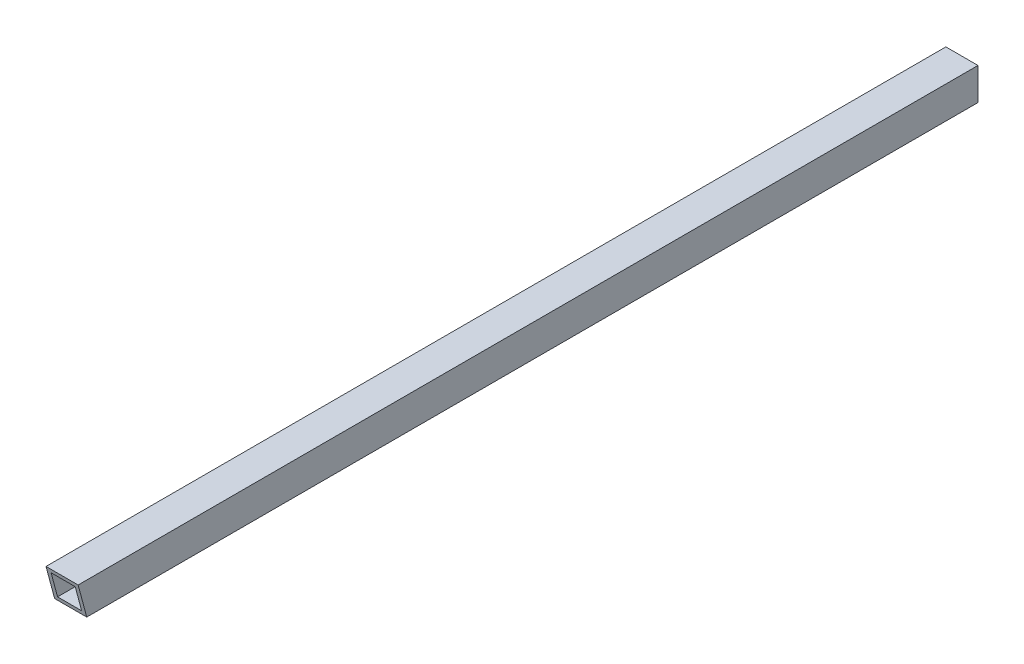
SolidWorks part; units mm, degrees
ref_plane "Front Plane" through (0, 0, 0) normal (0, 0, 1) x (1, 0, 0)
ref_plane "Top Plane" through (0, 0, 0) normal (0, 1, 0) x (1, 0, 0)
ref_plane "Right Plane" through (0, 0, 0) normal (1, 0, 0) x (0, 0, -1)
sketch "Sketch1" plane through (0, 0, 0) normal (0, 0, 1) x (1, 0, 0)
  line L1 (12.7, -12.7) -> (-12.7, -12.7)
  line L2 (12.7, -12.7) -> (12.7, 12.7)
  line L3 (12.7, 12.7) -> (-12.7, 12.7)
  line L4 (-12.7, -12.7) -> (-12.7, 12.7)
  line L5 (12.7, -12.7) -> (-12.7, 12.7) construction
  line L6 (12.7, 12.7) -> (-12.7, -12.7) construction
  line L7 (9.525, -9.525) -> (-9.525, -9.525)
  line L8 (9.525, -9.525) -> (9.525, 9.525)
  line L9 (9.525, 9.525) -> (-9.525, 9.525)
  line L10 (-9.525, -9.525) -> (-9.525, 9.525)
  line L11 (9.525, -9.525) -> (-9.525, 9.525) construction
  line L12 (9.525, 9.525) -> (-9.525, -9.525) construction
  point P0 (0, 0)
  point P6 (0, 0)
  dimension "D1" = 25.4
  dimension "D2" = 3.175
extrude "Boss-Extrude1" add sketch "Sketch1" along normal blind 711.2
ref_plane "Plane1" through (0, -176.9493, 660.3836) normal (0, -0.2588, 0.9659) x (-1, 0, 0)
sketch "Sketch2" plane through (0, 0, 711.2) normal (0, 0, 1) x (1, 0, 0)
  line L0 (-9.525, 9.525) -> (-9.525, -9.525) construction
  line L1 (-12.7, 12.7) -> (-12.7, -12.7) construction
  line L2 (-12.7, -12.7) -> (12.7, -12.7) construction
  line L3 (12.7, -12.7) -> (12.7, 12.7) construction
  line L4 (-9.525, -9.525) -> (9.525, -9.525)
  line L5 (-9.525, 9.525) -> (-9.525, -9.525)
  line L6 (9.525, 9.525) -> (-9.525, 9.525)
  line L7 (9.525, -9.525) -> (9.525, 9.525)
  line L8 (-9.525, -9.525) -> (9.525, -9.525)
  line L9 (-9.525, 9.525) -> (-9.525, -9.525)
  line L10 (9.525, 9.525) -> (-9.525, 9.525)
  line L11 (9.525, -9.525) -> (9.525, 9.525)
  line L12 (12.7, 12.7) -> (-12.7, 12.7) construction
  line L13 (-9.525, 9.525) -> (-9.525, -9.525)
  line L14 (-12.7, 12.7) -> (-12.7, -12.7)
  line L15 (-12.7, -12.7) -> (12.7, -12.7)
  line L16 (12.7, -12.7) -> (12.7, 12.7)
  line L17 (12.7, 12.7) -> (-12.7, 12.7)
  dimension "D1" = 0
sketch "Sketch3" plane through (0, -176.9493, 660.3836) normal (0, -0.2588, 0.9659) x (-1, 0, 0)
  line L0 (-12.7, -196.3394) -> (12.7, -196.3394)
  line L1 (-12.7, -196.3394) -> (12.7, -196.3394)
  line L2 (12.7, -170.0433) -> (12.7, -196.3394)
  line L3 (12.7, -170.0433) -> (12.7, -196.3394)
  line L4 (-12.7, -170.0433) -> (12.7, -170.0433)
  line L5 (-12.7, -170.0433) -> (12.7, -170.0433)
  line L6 (-12.7, -196.3394) -> (-12.7, -170.0433)
  line L7 (-12.7, -196.3394) -> (-12.7, -170.0433)
extrude "Cut-Extrude2" cut sketch "Sketch3" along normal through all
